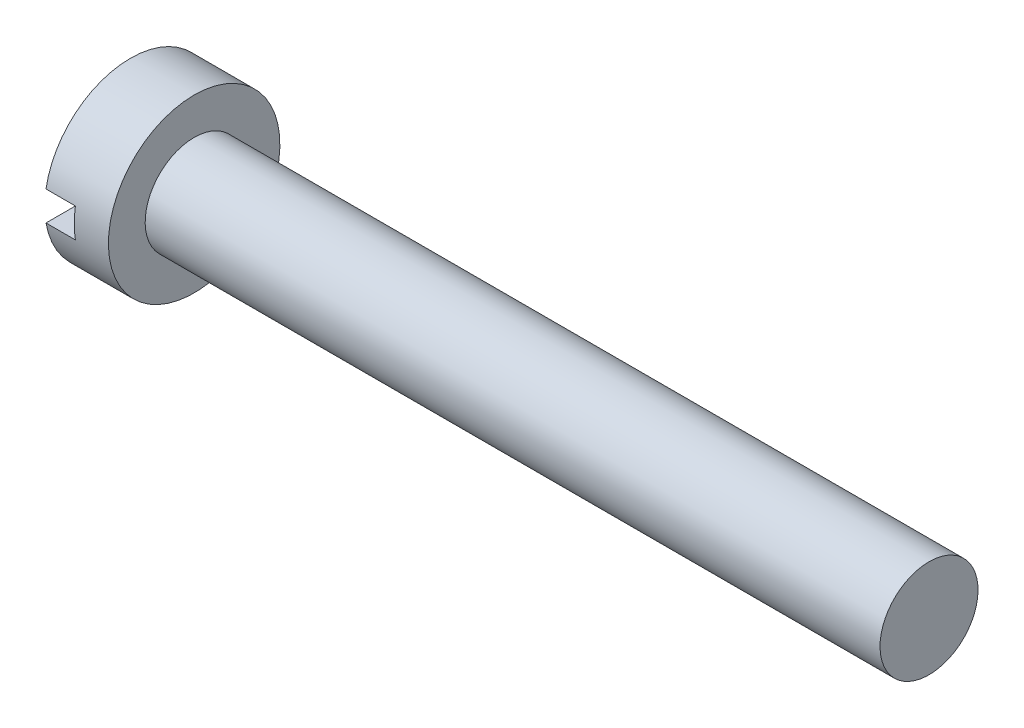
SolidWorks part; units mm, degrees
material "Plain Carbon Steel"
ref_plane "Front Plane" through (0, 0, 0) normal (0, 0, 1) x (1, 0, 0)
ref_plane "Top Plane" through (0, 0, 0) normal (0, 1, 0) x (1, 0, 0)
ref_plane "Right Plane" through (0, 0, 0) normal (1, 0, 0) x (0, 0, -1)
sketch "Sketch1" plane through (0, 0, 0) normal (0, 0, 1) x (1, 0, 0)
  line L0 (0, 0) -> (0, 3.5)
  line L1 (0, 3.5) -> (2.6, 3.5)
  line L2 (2.6, 3.5) -> (2.6, 2)
  line L3 (2.6, 2) -> (32.6, 2)
  line L4 (32.6, 2) -> (32.6, 0)
  line L5 (32.6, 0) -> (0, 0) construction
  line L6 (0, 0) -> (32.6, 0)
  dimension "D1" = 4
  dimension "D2" = 30
  dimension "D3" = 7
  dimension "D4" = 2.6
revolve "Revolve1" add sketch "Sketch1" angle 360 about L5
sketch "Sketch2" plane through (0, 0, 0) normal (-1, 0, 0) x (0, 0, 1)
  line L0 (3.5, 0) -> (-3.5, 0) construction
  line L1 (-3.5, 0.6) -> (3.5, 0.6)
  line L2 (-3.5, 0.6) -> (-3.5, -0.6)
  line L3 (-3.5, -0.6) -> (3.5, -0.6)
  line L4 (3.5, 0.6) -> (3.5, -0.6)
  circle A0 centre (0, 0) radius 3.5 construction
  dimension "D1" = 1.2
extrude "Cut-Extrude1" cut sketch "Sketch2" against normal blind 1.2
